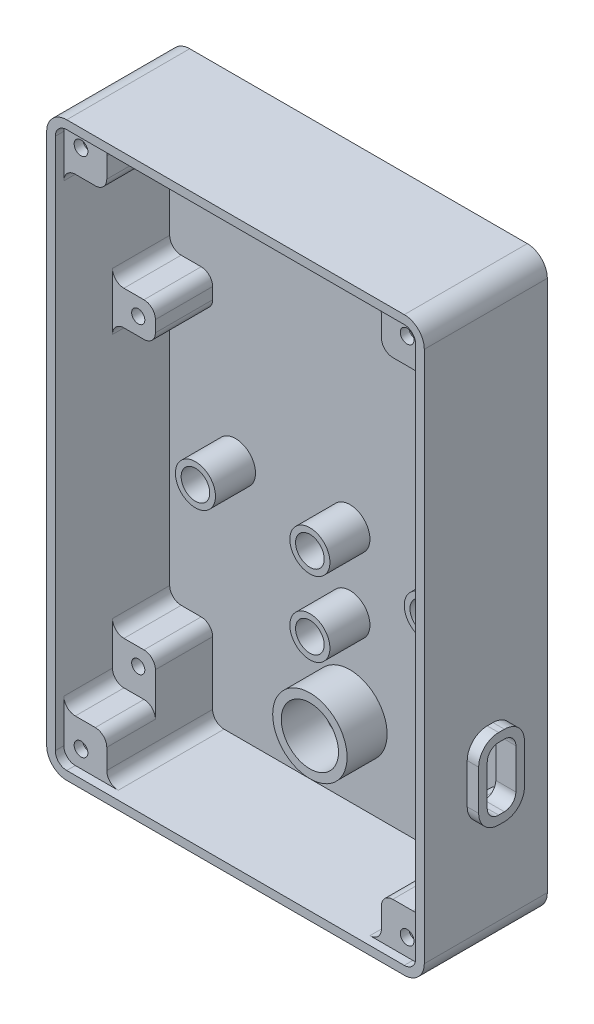
SolidWorks part; units mm, degrees
material "ABS"
ref_plane "Спереди" through (0, 0, 0) normal (0, 0, 1) x (1, 0, 0)
ref_plane "Сверху" through (0, 0, 0) normal (0, 1, 0) x (1, 0, 0)
ref_plane "Справа" through (0, 0, 0) normal (1, 0, 0) x (0, 0, -1)
sketch "Эскиз1" plane through (0, 0, 0) normal (0, 0, 1) x (1, 0, 0)
  line L1 (-33, -50) -> (33, -50)
  line L2 (-33, -50) -> (-33, 50)
  line L3 (-33, 50) -> (33, 50)
  line L4 (33, -50) -> (33, 50)
  line L5 (-33, -50) -> (33, 50) construction
  line L6 (-33, 50) -> (33, -50) construction
  line L7 (-31.5, -48.5) -> (31.5, -48.5)
  line L8 (-31.5, -48.5) -> (-31.5, 48.5)
  line L9 (-31.5, 48.5) -> (31.5, 48.5)
  line L10 (31.5, -48.5) -> (31.5, 48.5)
  line L11 (-31.5, -48.5) -> (31.5, 48.5) construction
  line L12 (-31.5, 48.5) -> (31.5, -48.5) construction
  point P0 (0, 0)
  point P6 (0, 0)
  dimension "D1" = 66
  dimension "D2" = 100
  dimension "D3" = 1.5
  dimension "D4" = 1.5
extrude "Бобышка-Вытянуть1" add sketch "Эскиз1" along normal blind 20
sketch "Эскиз3" plane through (0, 0, 0) normal (0, 0, -1) x (-1, 0, 0)
  line L1 (-33, 50) -> (33, 50)
  line L2 (-33, 50) -> (-33, -50)
  line L3 (-33, -50) -> (33, -50)
  line L4 (33, 50) -> (33, -50)
extrude "Бобышка-Вытянуть2" add sketch "Эскиз3" along normal blind 1.5
sketch "Эскиз4" plane through (0, 0, 0) normal (0, 0, 1) x (1, 0, 0)
  line L0 (-31.5, 48.5) -> (-31.5, -48.5) construction
  line L1 (-31.5, 19.5) -> (-24, 19.5)
  line L2 (-31.5, 19.5) -> (-31.5, 13.5)
  line L3 (-31.5, 13.5) -> (-24, 13.5)
  line L4 (-24, 19.5) -> (-24, 13.5)
  line L5 (31.5, -48.5) -> (31.5, 48.5) construction
  line L6 (31.5, 19.5) -> (24, 19.5)
  line L7 (31.5, 19.5) -> (31.5, 13.5)
  line L8 (31.5, 13.5) -> (24, 13.5)
  line L9 (24, 19.5) -> (24, 13.5)
  line L10 (-31.5, -48.5) -> (31.5, -48.5) construction
  line L11 (-31.5, -41) -> (-24, -41)
  line L12 (-31.5, -41) -> (-31.5, -33.5)
  line L13 (-31.5, -33.5) -> (-24, -33.5)
  line L14 (-24, -41) -> (-24, -33.5)
  line L15 (31.5, -41) -> (24, -41)
  line L16 (31.5, -41) -> (31.5, -33.5)
  line L17 (31.5, -33.5) -> (24, -33.5)
  line L18 (24, -41) -> (24, -33.5)
  line L19 (31.5, -48.5) -> (31.5, 48.5) construction
  dimension "D1" = 7.5
  dimension "D2" = 7.5
  dimension "D3" = 6
  dimension "D4" = 47
  dimension "D5" = 7.5
extrude "Бобышка-Вытянуть3" add sketch "Эскиз4" along normal blind 10
sketch "Эскиз5" plane through (0, 0, 10) normal (0, 0, 1) x (1, 0, 0)
  line L0 (-24, 13.5) -> (-24, 19.5) construction
  line L1 (24, 19.5) -> (24, 13.5) construction
  line L2 (-31.5, 13.5) -> (-24, 13.5) construction
  line L3 (-24, -33.5) -> (-31.5, -33.5) construction
  point P0 (-27, 16.5)
  point P1 (27, 16.5)
  point P2 (27, -36.5)
  point P3 (-27, -36.5)
  dimension "D1" = 3
  dimension "D2" = 3
  dimension "D3" = 3
  dimension "D4" = 3
hole_wizard "Сверло под метчик  спиральное M2.21" positions "Эскиз6" profile "Эскиз7" hole size "M2.2x0.45" standard "DIN"
sketch "Эскиз6" plane through (0, 0, 10) normal (0, 0, 1) x (1, 0, 0)
  point P0 (-27, 16.5)
  point P3 (27, 16.5)
  point P6 (27, -36.5)
  point P9 (-27, -36.5)
sketch "Эскиз7" plane through (-27, 16.5, 10) normal (1, 0, 0) x (0, -1, 0)
  line L0 (0, 0) -> (0, 4.691)
  line L1 (0, 4.691) -> (1.15, 4)
  line L2 (1.15, 4) -> (1.15, 0)
  line L5 (1.15, 0) -> (0, 0)
  line L10 (0, 4.691) -> (-1.15, 4) construction
  line L11 (0, -6.35) -> (0, 107.95) construction
  dimension "Диаметр отверстия" = 2.3
  dimension "Глубина отверстия" = 4
  dimension "Угол заточки сверла" = 118
sketch "Эскиз8" plane through (0, 0, 0) normal (0, 0, 1) x (1, 0, 0)
  line L0 (-24, -41) -> (-24, -33.5) construction
  line L1 (-31.5, 48.5) -> (-24, 48.5)
  line L2 (-31.5, 48.5) -> (-31.5, 41)
  line L3 (-31.5, 41) -> (-24, 41)
  line L4 (-24, 48.5) -> (-24, 41)
  line L5 (31.5, 48.5) -> (24, 48.5)
  line L6 (31.5, 48.5) -> (31.5, 41)
  line L7 (31.5, 41) -> (24, 41)
  line L8 (24, 48.5) -> (24, 41)
  line L9 (31.5, -48.5) -> (24, -48.5)
  line L10 (31.5, -48.5) -> (31.5, -41)
  line L11 (31.5, -41) -> (24, -41)
  line L12 (24, -48.5) -> (24, -41)
  line L13 (-31.5, -48.5) -> (-24, -48.5)
  line L14 (-31.5, -48.5) -> (-31.5, -41)
  line L15 (-31.5, -41) -> (-24, -41)
  line L16 (-24, -48.5) -> (-24, -41)
  line L18 (24, -33.5) -> (24, -41) construction
  line L19 (-24, 19.5) -> (-31.5, 19.5) construction
  line L21 (-31.5, -41) -> (-24, -41) construction
extrude "Бобышка-Вытянуть4" add sketch "Эскиз8" along normal blind 18.5
fillet "Скругление1" radius 2 20 edges at (-31.5, -33.5, 5) (-24, -33.5, 5) (-24, -48.5, 9.25) (24, -48.5, 9.25) (24, -33.5, 5) (31.5, -33.5, 5) (31.5, 13.5, 5) (24, 13.5, 5) (24, 19.5, 5) (31.5, 19.5, 5) (-31.5, 13.5, 5) (-24, 13.5, 5) (-24, 19.5, 5) (-31.5, 19.5, 5) (-31.5, 41, 9.25) (-24, 41, 9.25) (-24, 48.5, 9.25) (31.5, 41, 9.25) (24, 48.5, 9.25) (24, 41, 9.25)
fillet "Скругление3" radius 2 8 edges at (-31.5, -48.5, 19.25) (-31.5, -41, 14.25) (-24, -41, 14.25) (31.5, -48.5, 19.25) (24, -41, 14.25) (31.5, -41, 14.25) (-31.5, 48.5, 19.25) (31.5, 48.5, 19.25)
fillet "Скругление4" radius 3.5 4 edges at (-33, -50, 9.25) (33, -50, 9.25) (33, 50, 9.25) (-33, 50, 9.25)
sketch "Эскиз9" plane through (0, 0, 0) normal (0, 0, 1) x (1, 0, 0)
  circle A0 centre (-20, -7) radius 2.5
  circle A1 centre (20, -7) radius 2.5
  circle A2 centre (0, -20) radius 2.5
  circle A3 centre (0, -7) radius 2.5
  circle A4 centre (0, -35) radius 3.5
  point P8 (0, 0)
  point P10 (0, -3.7843)
  dimension "D1" = 5
  dimension "D6" = 7
  dimension "D2" = 7
  dimension "D3" = 20
  dimension "D4" = 20
  dimension "D5" = 20
  dimension "D7" = 35
extrude "Вырез-Вытянуть1" cut sketch "Эскиз9" against normal through all
sketch "Эскиз10" plane through (0, 0, 0) normal (0, 0, 1) x (1, 0, 0)
  circle A0 centre (-20, -7) radius 2.5
  circle A2 centre (0, -7) radius 2.5
  circle A3 centre (20, -7) radius 2.5
  circle A4 centre (0, -20) radius 2.5
  circle A5 centre (-20, -7) radius 2.5 construction
  circle A6 centre (0, -7) radius 3.5
  circle A7 centre (20, -7) radius 3.5
  circle A8 centre (0, -20) radius 3.5
  circle A9 centre (-20, -7) radius 3.5
  dimension "D1" = 1
extrude "Бобышка-Вытянуть5" add sketch "Эскиз10" along normal blind 7
sketch "Эскиз11" plane through (0, 0, -1.5) normal (0, 0, -1) x (-1, 0, 0)
  line L0 (29.5, 50) -> (-29.5, 50) construction
  line L1 (33, -46.5) -> (33, 46.5) construction
  line L2 (-29.5, -50) -> (29.5, -50) construction
  line L3 (-33, 46.5) -> (-33, -46.5) construction
  circle A0 centre (-28.5, 45.5) radius 2.5
  circle A1 centre (28.5, 45.5) radius 2.5
  circle A2 centre (28.5, -45.5) radius 2.5
  circle A3 centre (-28.5, -45.5) radius 2.5
  dimension "D2" = 5
  dimension "D1" = 4.5
  dimension "D3" = 4.5
  dimension "D4" = 4.5
  dimension "D5" = 4.5
extrude "Вырез-Вытянуть2" cut sketch "Эскиз11" against normal blind 18.5
sketch "Эскиз12" plane through (0, 0, 17) normal (0, 0, -1) x (-1, 0, 0)
  point P0 (-28.5, 45.5)
  point P1 (28.5, 45.5)
  point P3 (28.5, -45.5)
  point P5 (-28.5, -45.5)
hole_wizard "Отверстие с зазором M21" positions "Эскиз13" profile "Эскиз14" hole size "M2" standard "DIN" end condition through all
sketch "Эскиз13" plane through (0, 0, 17) normal (0, 0, -1) x (-1, 0, 0)
  point P0 (-28.5, 45.5)
  point P3 (28.5, 45.5)
  point P6 (28.5, -45.5)
  point P9 (-28.5, -45.5)
sketch "Эскиз14" plane through (28.5, 45.5, 17) normal (1, 0, 0) x (0, 1, 0)
  line L0 (0, 0) -> (0, 3)
  line L1 (0, 3) -> (1.2, 3)
  line L2 (1.2, 3) -> (1.2, 0)
  line L5 (1.2, 0) -> (0, 0)
  line L11 (0, -6.35) -> (0, 107.95) construction
  dimension "Диаметр сквозного отверстия" = 2.4
  dimension "Глубина сквозного отверстия" = 3
sketch "Эскиз15" plane through (31.5, 0, 0) normal (-1, 0, 0) x (0, 0, 1)
  line L1 (6, -28.5) -> (11, -28.5)
  line L2 (6, -28.5) -> (6, -17.5)
  line L3 (6, -17.5) -> (11, -17.5)
  line L4 (11, -28.5) -> (11, -17.5)
  line L5 (10, -39) -> (10, -31.5) construction
  dimension "D1" = 5
  dimension "D2" = 11
  dimension "D3" = 8
  dimension "D4" = 1
extrude "Вырез-Вытянуть3" cut sketch "Эскиз15" against normal through all
fillet "Скругление5" radius 2 4 edges at (32.25, -28.5, 11) (32.25, -17.5, 11) (32.25, -17.5, 6) (32.25, -28.5, 6)
sketch "Эскиз16" plane through (0, 0, 0) normal (0, 0, 1) x (1, 0, 0)
  circle A0 centre (0, -35) radius 5
  circle A1 centre (0, -35) radius 6.5
  dimension "D1" = 1.5
  dimension "D2" = 10
extrude "Бобышка-Вытянуть6" add sketch "Эскиз16" along normal blind 7
sketch "Эскиз19" plane through (33, 0, 0) normal (1, 0, 0) x (0, 0, -1)
  line L8 (-11, -19.5) -> (-11, -26.5)
  line L9 (-9, -28.5) -> (-8, -28.5)
  line L10 (-6, -26.5) -> (-6, -19.5)
  line L11 (-8, -17.5) -> (-9, -17.5)
  line L12 (-11, -19.5) -> (-11, -26.5)
  line L13 (-9, -28.5) -> (-8, -28.5)
  line L14 (-6, -26.5) -> (-6, -19.5)
  line L15 (-8, -17.5) -> (-9, -17.5)
  line L24 (-4.5, -26.5) -> (-4.5, -19.5)
  line L25 (-9, -30) -> (-8, -30)
  line L26 (-12.5, -19.5) -> (-12.5, -26.5)
  line L27 (-8, -16) -> (-9, -16)
  line L28 (-4.5, -26.5) -> (-4.5, -19.5)
  line L29 (-9, -30) -> (-8, -30)
  line L30 (-12.5, -19.5) -> (-12.5, -26.5)
  line L31 (-8, -16) -> (-9, -16)
  arc A8 (-11, -26.5) -> (-9, -28.5) centre (-9, -26.5) ccw
  arc A9 (-8, -28.5) -> (-6, -26.5) centre (-8, -26.5) ccw
  arc A10 (-6, -19.5) -> (-8, -17.5) centre (-8, -19.5) ccw
  arc A11 (-9, -17.5) -> (-11, -19.5) centre (-9, -19.5) ccw
  arc A12 (-11, -26.5) -> (-9, -28.5) centre (-9, -26.5) ccw
  arc A13 (-8, -28.5) -> (-6, -26.5) centre (-8, -26.5) ccw
  arc A14 (-6, -19.5) -> (-8, -17.5) centre (-8, -19.5) ccw
  arc A15 (-9, -17.5) -> (-11, -19.5) centre (-9, -19.5) ccw
  arc A20 (-4.5, -19.5) -> (-8, -16) centre (-8, -19.5) ccw
  arc A21 (-8, -30) -> (-4.5, -26.5) centre (-8, -26.5) ccw
  arc A22 (-12.5, -26.5) -> (-9, -30) centre (-9, -26.5) ccw
  arc A23 (-9, -16) -> (-12.5, -19.5) centre (-9, -19.5) ccw
  arc A24 (-4.5, -19.5) -> (-8, -16) centre (-8, -19.5) ccw
  arc A25 (-8, -30) -> (-4.5, -26.5) centre (-8, -26.5) ccw
  arc A26 (-12.5, -26.5) -> (-9, -30) centre (-9, -26.5) ccw
  arc A27 (-9, -16) -> (-12.5, -19.5) centre (-9, -19.5) ccw
  dimension "D1" = 1.5
  dimension "D2" = 0
extrude "Бобышка-Вытянуть7" add sketch "Эскиз19" along normal blind 2
